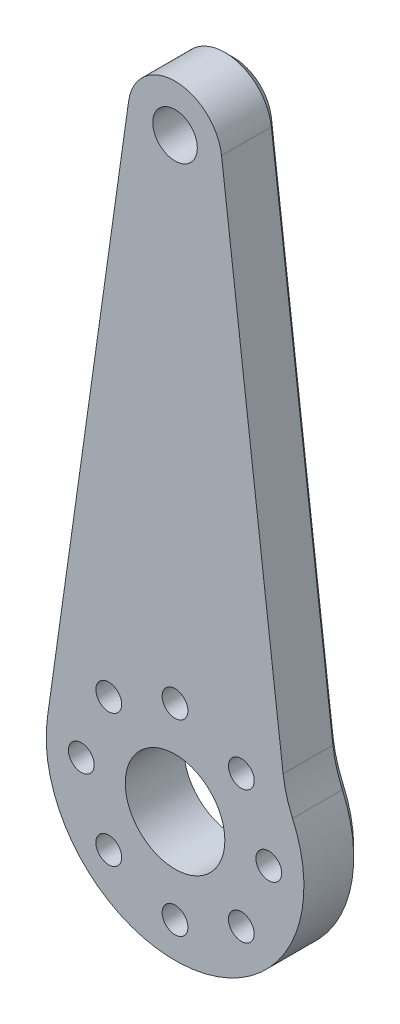
SolidWorks part; units mm, degrees
ref_plane "Front Plane" through (0, 0, 0) normal (0, 0, 1) x (1, 0, 0)
ref_plane "Top Plane" through (0, 0, 0) normal (0, 1, 0) x (1, 0, 0)
ref_plane "Right Plane" through (0, 0, 0) normal (1, 0, 0) x (0, 0, -1)
sketch "Sketch1" plane through (0, 0, 0) normal (0, 0, 1) x (1, 0, 0)
  line L0 (-19.0104, 30.5961) -> (-25.9414, -18.4239)
  line L3 (-11.0892, 30.5961) -> (-4.1581, -18.4239)
  line L4 (-15.0498, 0.8298) -> (-15.0498, 20.8298) construction
  line L5 (-14.6985, -19.9639) -> (49985.3015, -19.9639) construction
  circle A2 centre (-15.0498, 30.0361) radius 1.9
  circle A3 centre (-15.0498, -19.9639) radius 4.25
  arc A5 (-11.0892, 30.5961) -> (-19.0104, 30.5961) centre (-15.0498, 30.0361) ccw
  arc A6 (-25.9414, -18.4239) -> (-4.1581, -18.4239) centre (-15.0498, -19.9639) ccw
  circle A7 centre (-15.0314, -20.0888) radius 11 construction
  circle A8 centre (-7.0498, -19.9639) radius 1.1
  circle A9 centre (-9.3929, -25.6208) radius 1.1
  circle A10 centre (-15.0498, -27.9639) radius 1.1
  circle A11 centre (-20.7066, -25.6208) radius 1.1
  circle A12 centre (-23.0498, -19.9639) radius 1.1
  circle A13 centre (-20.7066, -14.307) radius 1.1
  circle A14 centre (-15.0498, -11.9639) radius 1.1
  circle A15 centre (-9.3929, -14.307) radius 1.1
  point P30 (-15.0498, -19.9639)
  dimension "D1" = 3.8
  dimension "D3" = 50
  dimension "D4" = 11
  dimension "D2" = 4
  dimension "D5" = 8.5
  dimension "D6" = 2.2
  dimension "D7" = 8
  dimension "D8" = 8
extrude "Boss-Extrude1" add sketch "Sketch1" along normal blind 5
sketch "Sketch2" plane through (0, 0, 5) normal (0, 0, 1) x (1, 0, 0)
  circle A0 centre (-15.0498, -19.9639) radius 11.5
  dimension "D1" = 23
extrude "Cut-Extrude1" [suppressed] cut sketch "Sketch2" against normal blind 1.75
sketch "Sketch5" plane through (0, 0, 5) normal (0, 0, 1) x (1, 0, 0)
  circle A2 centre (-14.8897, 3.8764) radius 1.55
  circle A3 centre (-14.8897, 3.8764) radius 8
extrude "Boss-Extrude2" [suppressed] add sketch "Sketch5" along normal blind 3
fillet "Fillet1" [suppressed] radius 1
sketch "Sketch4" plane through (0, 0, 0) normal (0, 0, -1) x (-1, 0, 0)
  circle A0 centre (23.0498, -19.9639) radius 1.75
  circle A1 centre (20.7066, -25.6208) radius 1.75
  circle A2 centre (15.0498, -27.9639) radius 1.75
  circle A3 centre (9.3929, -25.6208) radius 1.75
  circle A4 centre (7.0498, -19.9639) radius 1.75
  circle A5 centre (9.3929, -14.307) radius 1.75
  circle A6 centre (15.0498, -11.9639) radius 1.75
  circle A7 centre (20.7066, -14.307) radius 1.75
  circle A10 centre (15.0498, -19.9639) radius 4.25 construction
  point P20 (15.0498, -19.9639)
  dimension "D1" = 3.5
extrude "Cut-Extrude3" cut sketch "Sketch4" against normal blind 2.25
sketch "Croquis1" plane through (0, 0, 0) normal (0, 0, -1) x (-1, 0, 0)
  line L0 (11.0792, 30.5203) -> (5.6124, -14.3127)
  line L1 (19.0104, 30.5961) -> (25.9414, -18.4239) construction
  line L2 (11.0892, 30.5961) -> (4.1581, -18.4239)
  arc A0 (11.0892, 30.5961) -> (11.0792, 30.5203) centre (15.0498, 30.0361) ccw
  arc A1 (4.1581, -18.4239) -> (5.6124, -14.3127) centre (15.0498, -19.9639) cw
  dimension "D1" = 15
extrude "Cortar-Extruir1" cut sketch "Croquis1" against normal blind 10
fillet "Redondeo1" radius 10 1 edges at (-5.6124, -14.3127, 2.5)
chamfer "Chaflán1" distance 0.75 angle 45 5 edges at (-22.4759, 6.0861, 0) (-13.5012, -30.8544, 0) (-15.0115, 34.0359, 0) (-8.453, 8.9827, 0) (-5.5322, -14.0323, 0)
